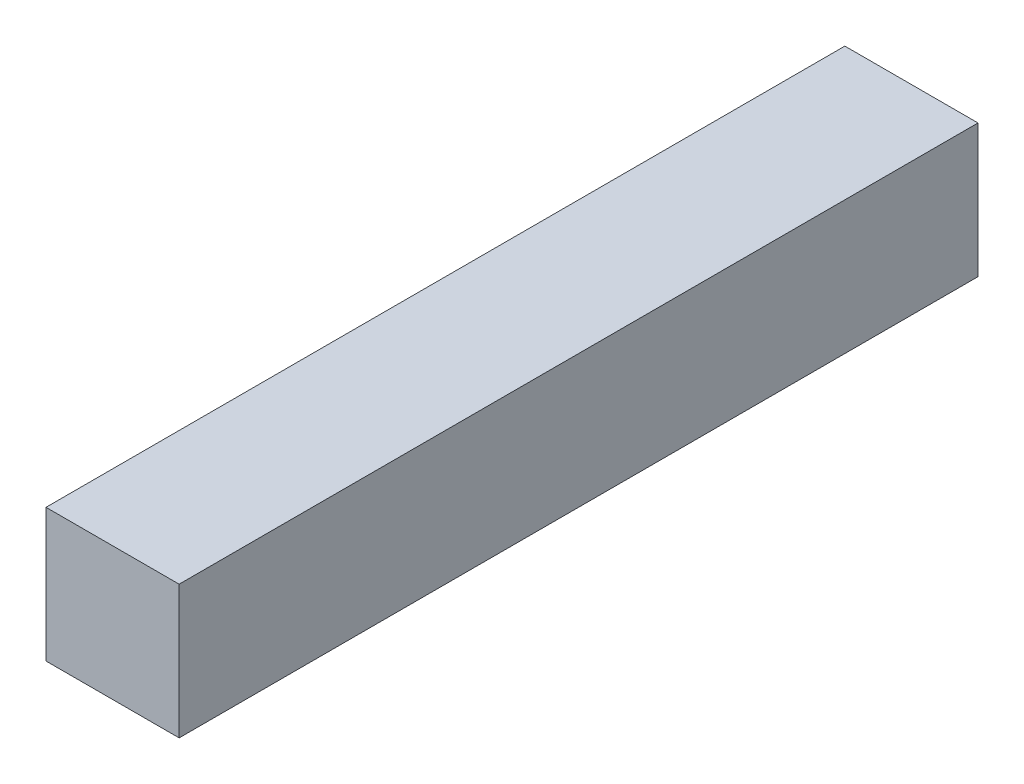
SolidWorks part; units mm, degrees
ref_plane "前视基准面" through (0, 0, 0) normal (0, 0, 1) x (1, 0, 0)
ref_plane "上视基准面" through (0, 0, 0) normal (0, 1, 0) x (1, 0, 0)
ref_plane "右视基准面" through (0, 0, 0) normal (1, 0, 0) x (0, 0, -1)
sketch "草图1" plane through (0, 0, 0) normal (0, 0, 1) x (1, 0, 0)
  line L1 (-5, -5) -> (5, -5)
  line L2 (-5, -5) -> (-5, 5)
  line L3 (-5, 5) -> (5, 5)
  line L4 (5, -5) -> (5, 5)
  line L5 (-5, -5) -> (5, 5) construction
  line L6 (-5, 5) -> (5, -5) construction
  point P0 (0, 0)
  dimension "D1" = 10
  dimension "D2" = 10
extrude "凸台-拉伸1" add sketch "草图1" along normal blind 60
